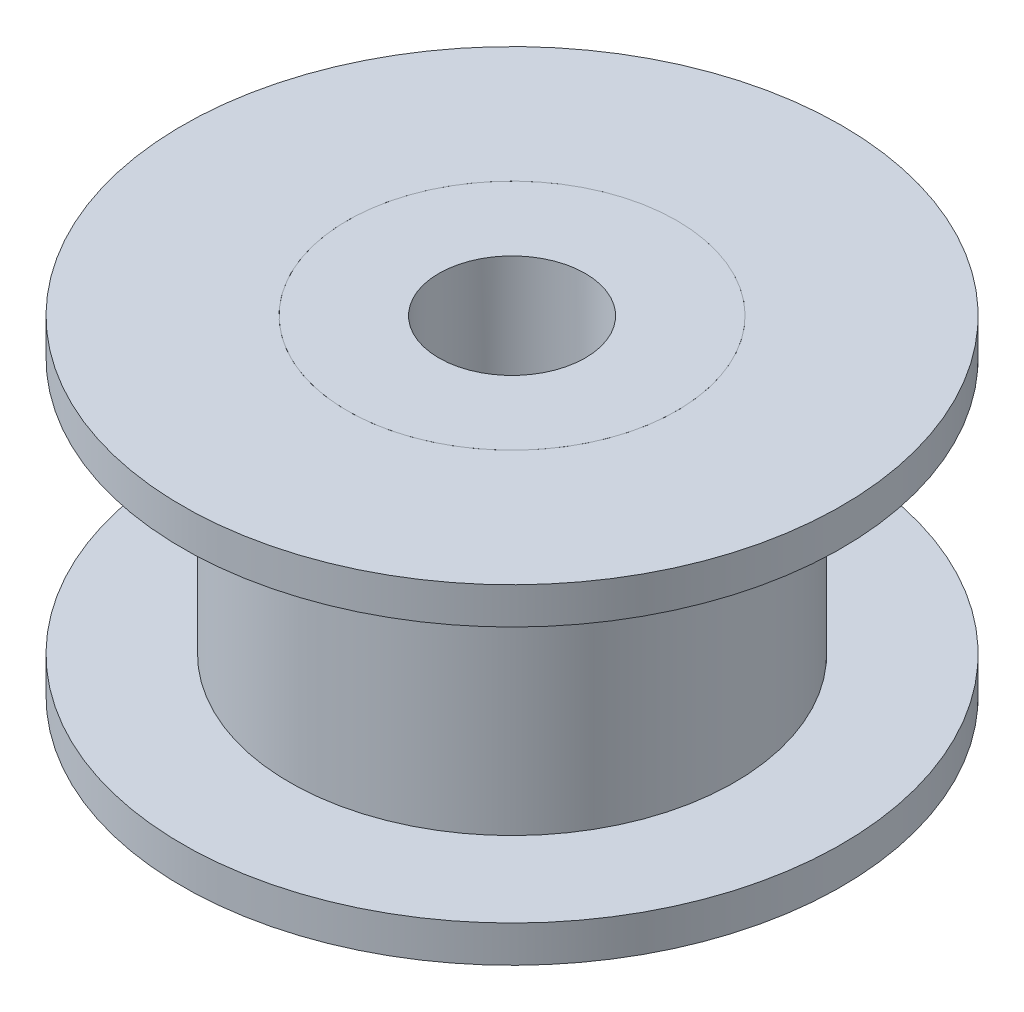
SolidWorks part; units mm, degrees
ref_plane "Plan de face" through (0, 0, 0) normal (0, 0, 1) x (1, 0, 0)
ref_plane "Plan de dessus" through (0, 0, 0) normal (0, 1, 0) x (1, 0, 0)
ref_plane "Plan de droite" through (0, 0, 0) normal (1, 0, 0) x (0, 0, -1)
sketch "Esquisse2" plane through (0, 0, 0) normal (0, 0, 1) x (1, 0, 0)
  line L8 (0, 0) -> (0, 5.8451) construction
  line L10 (2.5, 1.5) -> (4.5, 1.5)
  line L11 (4.5, 1.5) -> (4.5, 4.5)
  line L12 (4.5, 4.5) -> (9, 4.5)
  line L13 (9, 4.5) -> (9, 3.5)
  line L14 (9, 3.5) -> (6.075, 3.5)
  line L15 (6.075, 3.5) -> (6.075, -3.5)
  line L16 (0, 0) -> (15.8437, 0) construction
  line L17 (9, -3.5) -> (6.075, -3.5)
  line L18 (9, -4.5) -> (9, -3.5)
  line L19 (4.5, -4.5) -> (9, -4.5)
  line L20 (4.5, -1.5) -> (4.5, -4.5)
  line L21 (2.5, -1.5) -> (4.5, -1.5)
  line L22 (2.5, 1.5) -> (2.5, -1.5)
  point P13 (6.075, 0)
  dimension "D1" = 5
  dimension "D2" = 9
  dimension "D3" = 9
  dimension "D4" = 7
  dimension "D5" = 18
  dimension "D6" = 3
  dimension "D7" = 12.15
revolve "Révolution1" add sketch "Esquisse2" angle 360 about L8
sketch "Esquisse3" plane through (0, -1.5, 0) normal (0, 1, 0) x (1, 0, 0)
  circle A3 centre (0, 0) radius 2
  circle A4 centre (0, 0) radius 4.5 construction
  circle A5 centre (0, 0) radius 4.5
  dimension "D1" = 4
extrude "Boss.-Extru.1" add sketch "Esquisse3" against normal up to surface (3 mm away) separate body up to face at (0, -4.5, -9)
mirror "Symétrie8" about plane through (0, 0, 0) normal (0, 1, 0) of bodies 103
